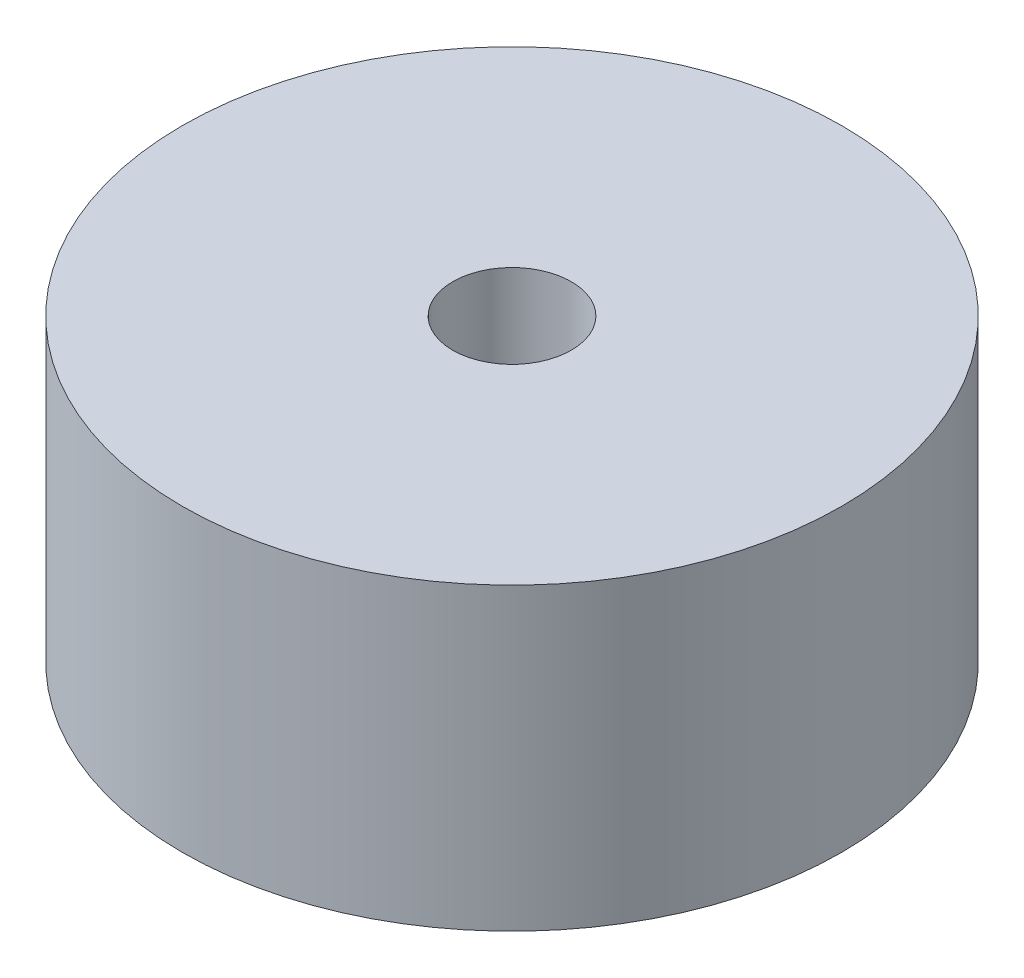
SolidWorks part; units mm, degrees
ref_plane "Front Plane" through (0, 0, 0) normal (0, 0, 1) x (1, 0, 0)
ref_plane "Top Plane" through (0, 0, 0) normal (0, 1, 0) x (1, 0, 0)
ref_plane "Right Plane" through (0, 0, 0) normal (1, 0, 0) x (0, 0, -1)
sketch "Sketch1" plane through (0, 0, 0) normal (0, 1, 0) x (1, 0, 0)
  line L0 (0, 0) -> (99.948, 0) construction
  circle A1 centre (0, 0) radius 0.99
  circle A2 centre (0, 0) radius 5.5
  dimension "D1" = 1.98
  dimension "D2" = 11
extrude "Boss-Extrude1" add sketch "Sketch1" along normal blind 5
